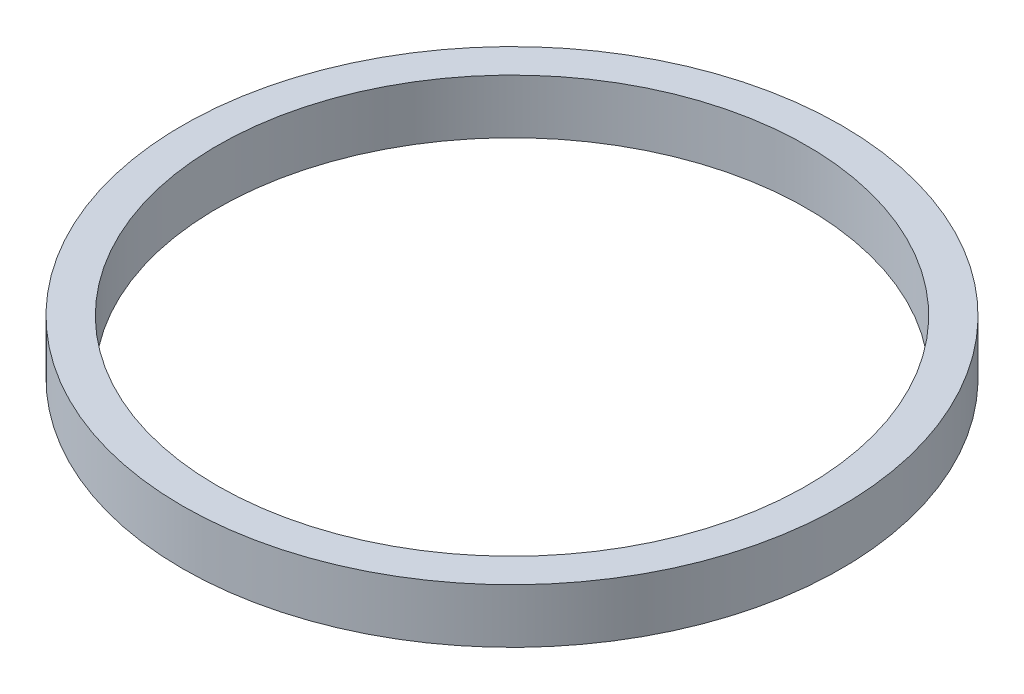
SolidWorks part; units mm, degrees
ref_plane "Front Plane" through (0, 0, 0) normal (0, 0, 1) x (1, 0, 0)
ref_plane "Top Plane" through (0, 0, 0) normal (0, 1, 0) x (1, 0, 0)
ref_plane "Right Plane" through (0, 0, 0) normal (1, 0, 0) x (0, 0, -1)
sketch "Sketch1" plane through (0, 0, 0) normal (0, 1, 0) x (1, 0, 0)
  circle A0 centre (0, 0) radius 42.5
  circle A1 centre (0, 0) radius 38
  dimension "D1" = 85
  dimension "D2" = 4.5
extrude "Boss-Extrude1" add sketch "Sketch1" along normal blind 7
